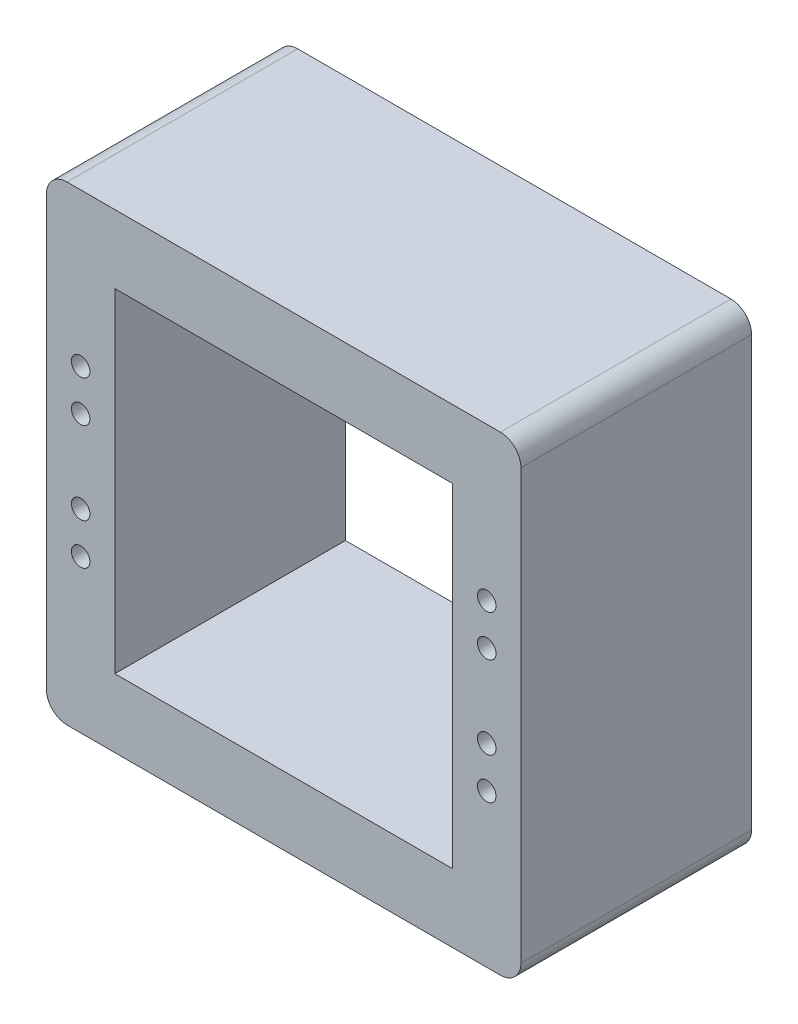
SolidWorks part; units mm, degrees
ref_plane "Front Plane" through (0, 0, 0) normal (0, 0, 1) x (1, 0, 0)
ref_plane "Top Plane" through (0, 0, 0) normal (0, 1, 0) x (1, 0, 0)
ref_plane "Right Plane" through (0, 0, 0) normal (1, 0, 0) x (0, 0, -1)
sketch "Sketch1" plane through (0, 0, 0) normal (0, 0, 1) x (1, 0, 0)
  line L0 (-8.3, -8.3) -> (49.3, -8.3)
  line L1 (0, 0) -> (41, 0)
  line L2 (0, 0) -> (0, 40.5)
  line L3 (0, 40.5) -> (41, 40.5)
  line L4 (41, 0) -> (41, 40.5)
  line L5 (49.3, -8.3) -> (49.3, 48.8)
  line L6 (-8.3, 48.8) -> (49.3, 48.8)
  line L7 (-8.3, -8.3) -> (-8.3, 48.8)
  line L8 (20.5, 48.8) -> (20.5, -8.3) construction
  line L9 (0, 20.25) -> (-8.3, 20.25) construction
  line L10 (-4.15, 20.25) -> (-4.15, 25.25) construction
  line L11 (-4.15, 25.25) -> (-4.15, 30.25) construction
  circle A0 centre (-4.15, 25.25) radius 1.125
  circle A1 centre (-4.15, 30.25) radius 1.125
  circle A2 centre (-4.15, 10.25) radius 1.125
  circle A3 centre (-4.15, 15.25) radius 1.125
  circle A4 centre (45.15, 15.25) radius 1.125
  circle A5 centre (45.15, 10.25) radius 1.125
  circle A6 centre (45.15, 30.25) radius 1.125
  circle A7 centre (45.15, 25.25) radius 1.125
  point P18 (-4.15, 30.25)
  dimension "D4" = 5
  dimension "D5" = 2.25
  dimension "D1" = 41
  dimension "D2" = 40.5
  dimension "D3" = 8.3
extrude "Boss-Extrude1" add sketch "Sketch1" along normal blind 28
fillet "Fillet1" radius 2.5 4 edges at (49.3, 48.8, 14) (49.3, -8.3, 14) (-8.3, -8.3, 14) (-8.3, 48.8, 14)
